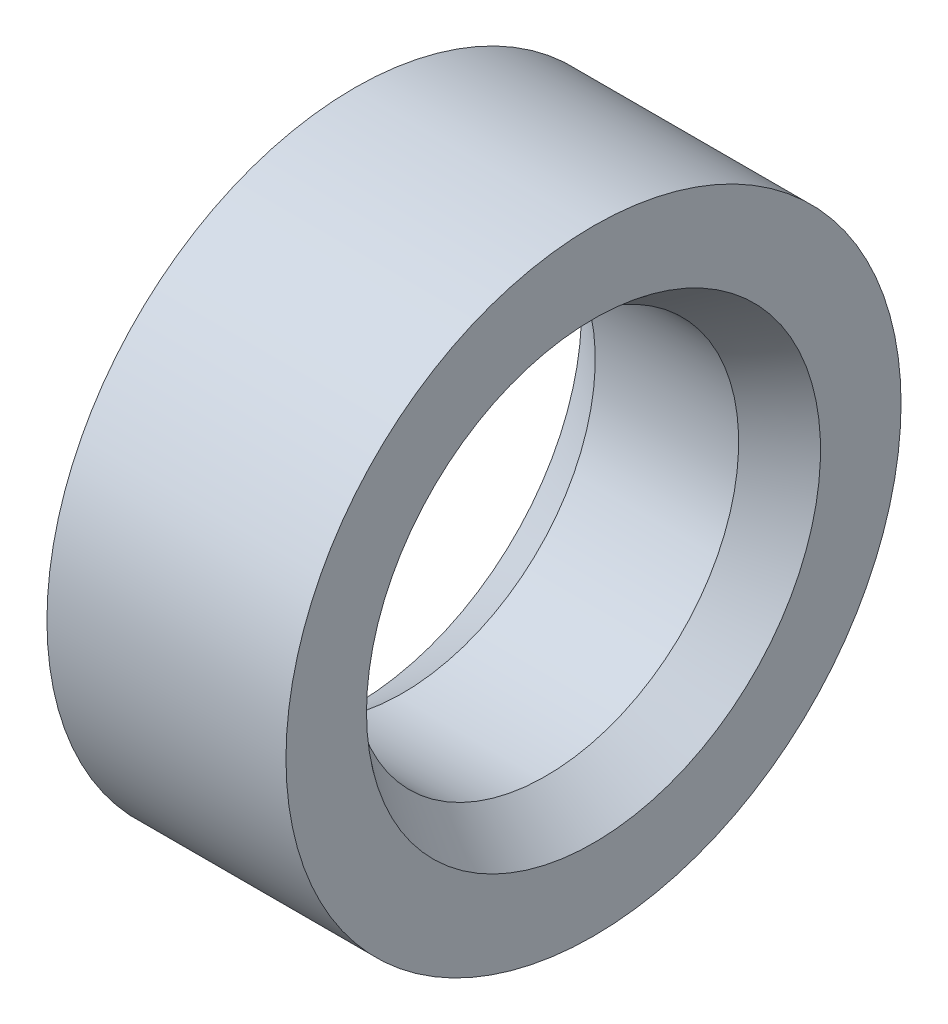
SolidWorks part; units mm, degrees
material "Найлон 6/10"
ref_plane "Спереди" through (0, 0, 0) normal (0, 0, 1) x (1, 0, 0)
ref_plane "Сверху" through (0, 0, 0) normal (0, 1, 0) x (1, 0, 0)
ref_plane "Справа" through (0, 0, 0) normal (1, 0, 0) x (0, 0, -1)
sketch "Эскиз1" plane through (0, 0, 0) normal (0, 0, 1) x (1, 0, 0)
  line L0 (-10.8471, 5) -> (-10.8471, 6.7736)
  line L1 (-10.8471, 6.7736) -> (-5.5827, 6.7736)
  line L2 (-5.5827, 6.7736) -> (-5.5827, 5)
  line L3 (-5.5827, 5) -> (-6.6356, 4.25)
  line L4 (-6.6356, 4.25) -> (-9.7942, 4.25)
  line L5 (-9.7942, 4.25) -> (-10.8471, 5)
  line L6 (-1000, 0) -> (49000, 0) construction
  point P5 (0, 0)
  point P6 (0, 0)
  point P7 (0, 0)
  point P14 (-6.4031, 2.4512)
  point P18 (0, 0)
  point P19 (-6.4031, 2.259)
  point P20 (-6.3719, 2.6434)
  point P21 (0, 0)
  point P22 (0, 0)
  point P23 (0, 0)
  point P24 (-5.9147, 2.3889)
  point P28 (0, 0)
  point P30 (0, 0)
  point P32 (0, 0)
revolve "Повернуть1" add sketch "Эскиз1" angle 360 about L6
